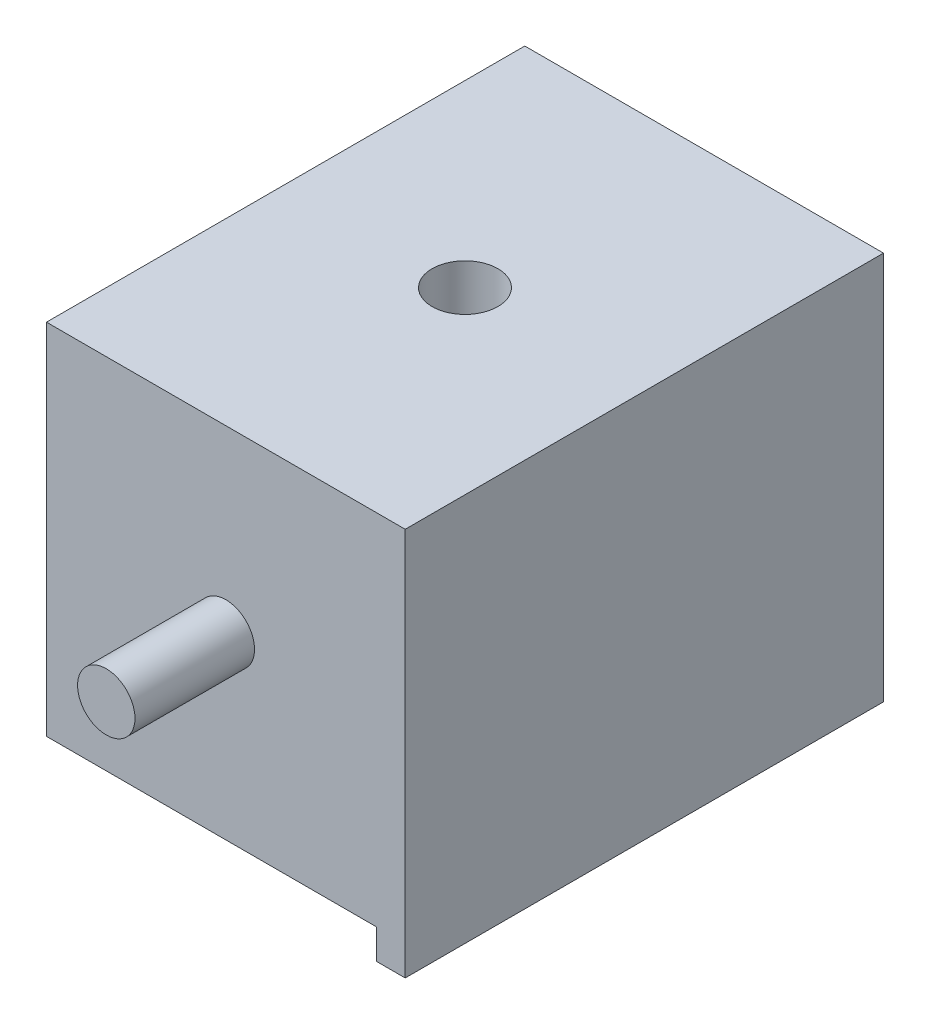
SolidWorks part; units mm, degrees
ref_plane "Front Plane" through (0, 0, 0) normal (0, 0, 1) x (1, 0, 0)
ref_plane "Top Plane" through (0, 0, 0) normal (0, 1, 0) x (1, 0, 0)
ref_plane "Right Plane" through (0, 0, 0) normal (1, 0, 0) x (0, 0, -1)
sketch "Sketch1" plane through (0, 0, 0) normal (0, 0, 1) x (1, 0, 0)
  line L5 (-19.05, -19.05) -> (19.05, -19.05)
  line L6 (-19.05, -19.05) -> (-19.05, 19.05)
  line L7 (-19.05, 19.05) -> (19.05, 19.05)
  line L8 (19.05, -19.05) -> (19.05, 19.05)
  line L9 (-19.05, -19.05) -> (19.05, 19.05) construction
  line L10 (-19.05, 19.05) -> (19.05, -19.05) construction
  point P4 (0, 0)
  dimension "D1" = 38.1
  dimension "D2" = 38.1
extrude "Boss-Extrude1" add sketch "Sketch1" along normal mid plane 50.8
sketch "Sketch2" plane through (0, 0, 25.4) normal (0, 0, 1) x (1, 0, 0)
  circle A0 centre (0, 0) radius 3.048
  dimension "D1" = 6.096
extrude "Boss-Extrude2" add sketch "Sketch2" along normal blind 12.7
ref_plane "Plane1" through (0, 0, 31.75) normal (0, 0, 1) x (1, 0, 0)
sketch "Sketch3" plane through (0, -19.05, 0) normal (0, -1, 0) x (1, 0, 0)
  line L0 (-19.05, 25.4) -> (19.05, 25.4) construction
  line L1 (19.05, -25.4) -> (16.002, -25.4)
  line L2 (19.05, -25.4) -> (19.05, 25.4)
  line L3 (19.05, 25.4) -> (16.002, 25.4)
  line L4 (16.002, -25.4) -> (16.002, 25.4)
  dimension "D1" = 3.048
extrude "Boss-Extrude3" add sketch "Sketch3" along normal blind 3.175
sketch "Sketch4" plane through (0, -19.05, 0) normal (0, -1, 0) x (1, 0, 0)
  circle A0 centre (0, 0) radius 3.4925
  dimension "D1" = 6.985
extrude "Cut-Extrude1" cut sketch "Sketch4" against normal through all
